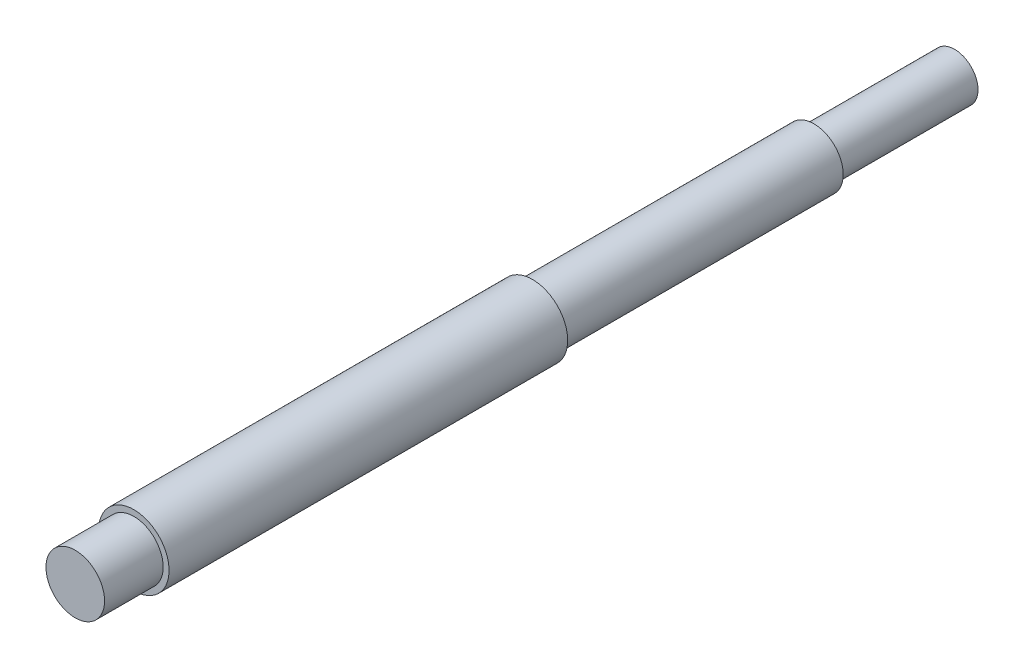
SolidWorks part; units mm, degrees
ref_plane "前视基准面" through (0, 0, 0) normal (0, 0, 1) x (1, 0, 0)
ref_plane "上视基准面" through (0, 0, 0) normal (0, 1, 0) x (1, 0, 0)
ref_plane "右视基准面" through (0, 0, 0) normal (1, 0, 0) x (0, 0, -1)
other "Configuration Table"
sketch "草图1" plane through (0, 0, 0) normal (0, 0, 1) x (1, 0, 0)
  circle A0 centre (0, 0) radius 2.5
  dimension "D1" = 5
extrude "凸台-拉伸1" add sketch "草图1" along normal blind 5
sketch "草图2" plane through (0, 0, 0) normal (0, 0, -1) x (-1, 0, 0)
  circle A0 centre (0, 0) radius 3
  dimension "D1" = 6
extrude "凸台-拉伸2" add sketch "草图2" along normal blind 34
sketch "草图3" plane through (0, 0, -34) normal (0, 0, -1) x (-1, 0, 0)
  circle A0 centre (0, 0) radius 2.5
  dimension "D1" = 5
extrude "凸台-拉伸3" add sketch "草图3" along normal blind 24
sketch "草图4" plane through (0, 0, -58) normal (0, 0, -1) x (-1, 0, 0)
  circle A0 centre (0, 0) radius 2
  dimension "D1" = 4
extrude "凸台-拉伸4" add sketch "草图4" along normal blind 12
